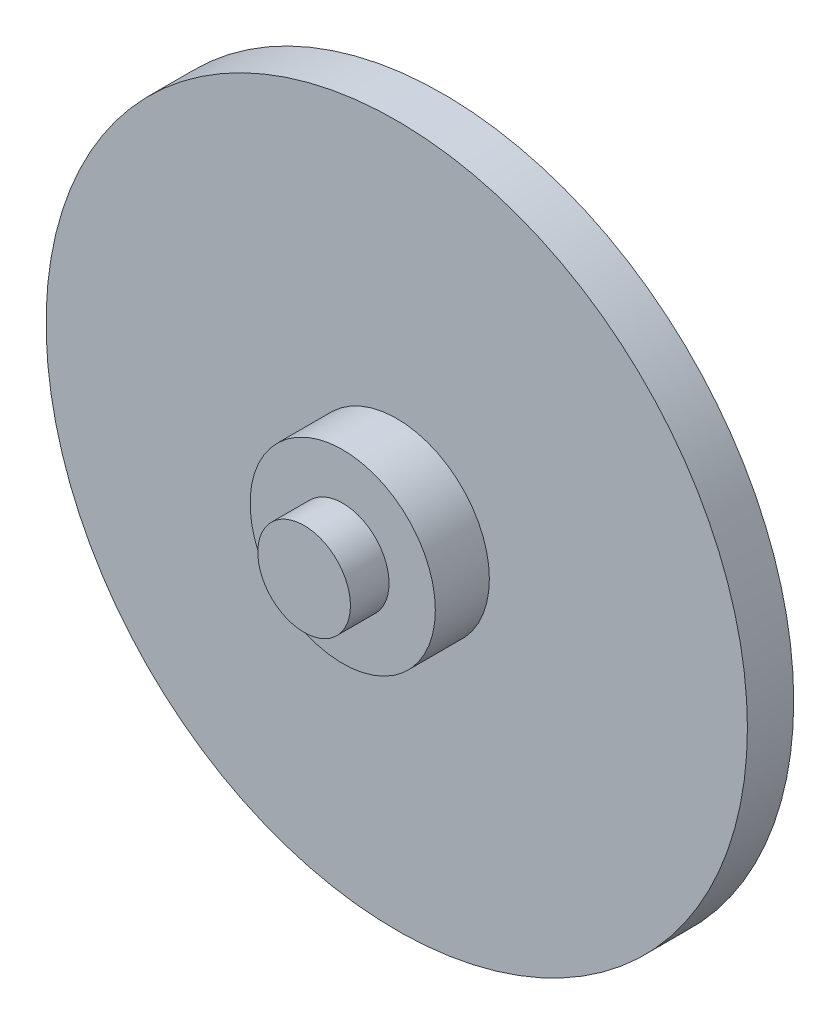
SolidWorks part; units mm, degrees
ref_plane "Front Plane" through (0, 0, 0) normal (0, 0, 1) x (1, 0, 0)
ref_plane "Top Plane" through (0, 0, 0) normal (0, 1, 0) x (1, 0, 0)
ref_plane "Right Plane" through (0, 0, 0) normal (1, 0, 0) x (0, 0, -1)
sketch "Sketch2" plane through (0, 0, 0) normal (0, 0, 1) x (1, 0, 0)
  circle A0 centre (-5.266, 0) radius 45.43
extrude "Boss-Extrude2" add sketch "Sketch2" along normal blind 6
sketch "Sketch3" plane through (0, 0, 6) normal (0, 0, 1) x (1, 0, 0)
  circle A1 centre (-5.266, 0) radius 12
extrude "Boss-Extrude3" add sketch "Sketch3" along normal blind 7 contours A1
sketch "Sketch4" plane through (0, 0, 13) normal (0, 0, 1) x (1, 0, 0)
  line L0 (-5.266, 12) -> (-5.266, 0) construction
  line L1 (-5.266, 0) -> (-17.266, 0) construction
  circle A0 centre (-5.266, 0) radius 12 construction
  circle A2 centre (-5.266, 0) radius 6
extrude "Boss-Extrude4" add sketch "Sketch4" along normal blind 5
sketch "Sketch5" plane through (0, 0, 0) normal (0, 0, -1) x (-1, 0, 0)
  line L0 (5.266, 45.43) -> (5.266, 0) construction
  line L1 (5.266, 0) -> (-40.164, 0) construction
  circle A0 centre (5.266, 0) radius 45.43 construction
  circle A1 centre (5.266, 0) radius 3
extrude "Cut-Extrude1" cut sketch "Sketch5" against normal blind 13
scale "Scale1" bodies to scale 105 scale about centroid uniform scaling yes scale factor 0.15
